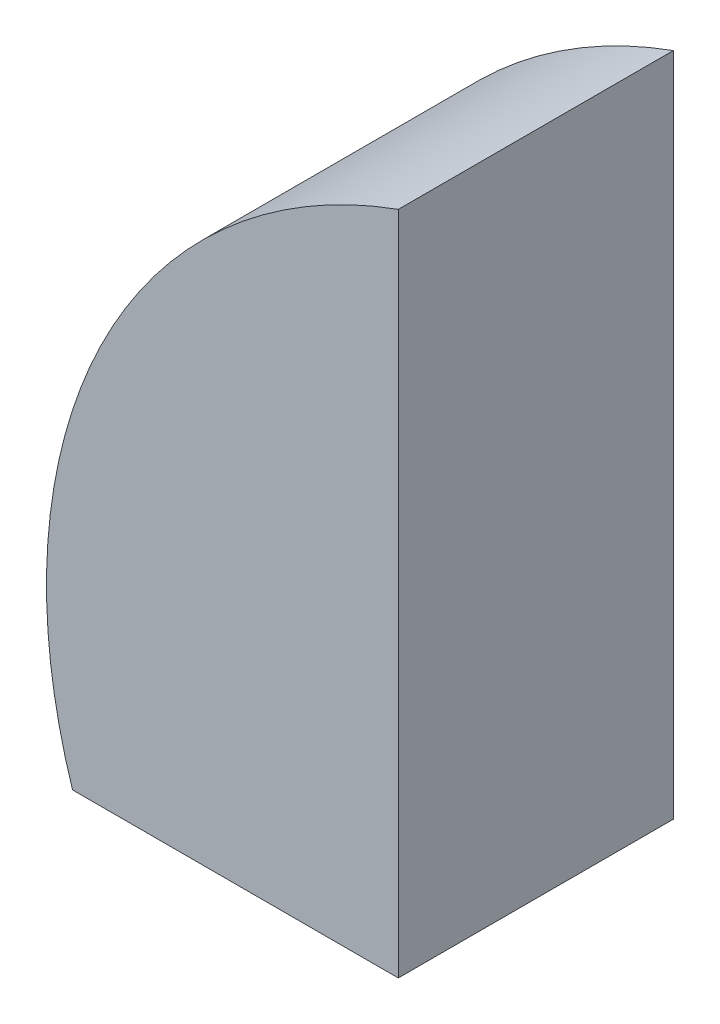
SolidWorks part; units mm, degrees
ref_plane "Front Plane" through (0, 0, 0) normal (0, 0, 1) x (1, 0, 0)
ref_plane "Top Plane" through (0, 0, 0) normal (0, 1, 0) x (1, 0, 0)
ref_plane "Right Plane" through (0, 0, 0) normal (1, 0, 0) x (0, 0, -1)
sketch "Sketch1" plane through (0, 0, 0) normal (0, 0, 1) x (1, 0, 0)
  line L0 (-1778, -577.5136) -> (1778, -577.5136)
  line L1 (-635, 1758.2892) -> (-635, -577.5136)
  line L2 (0, 1869.44) -> (0, -1869.44) construction
  line L3 (635, 1758.2892) -> (635, -577.5136)
  circle A0 centre (0, 0) radius 1869.44
  dimension "D1" = 3738.88
  dimension "D2" = 3556
  dimension "D3" = 1143
extrude "Boss-Extrude1" add sketch "Sketch1" along normal blind 965.2 contours L1 A0 L0
